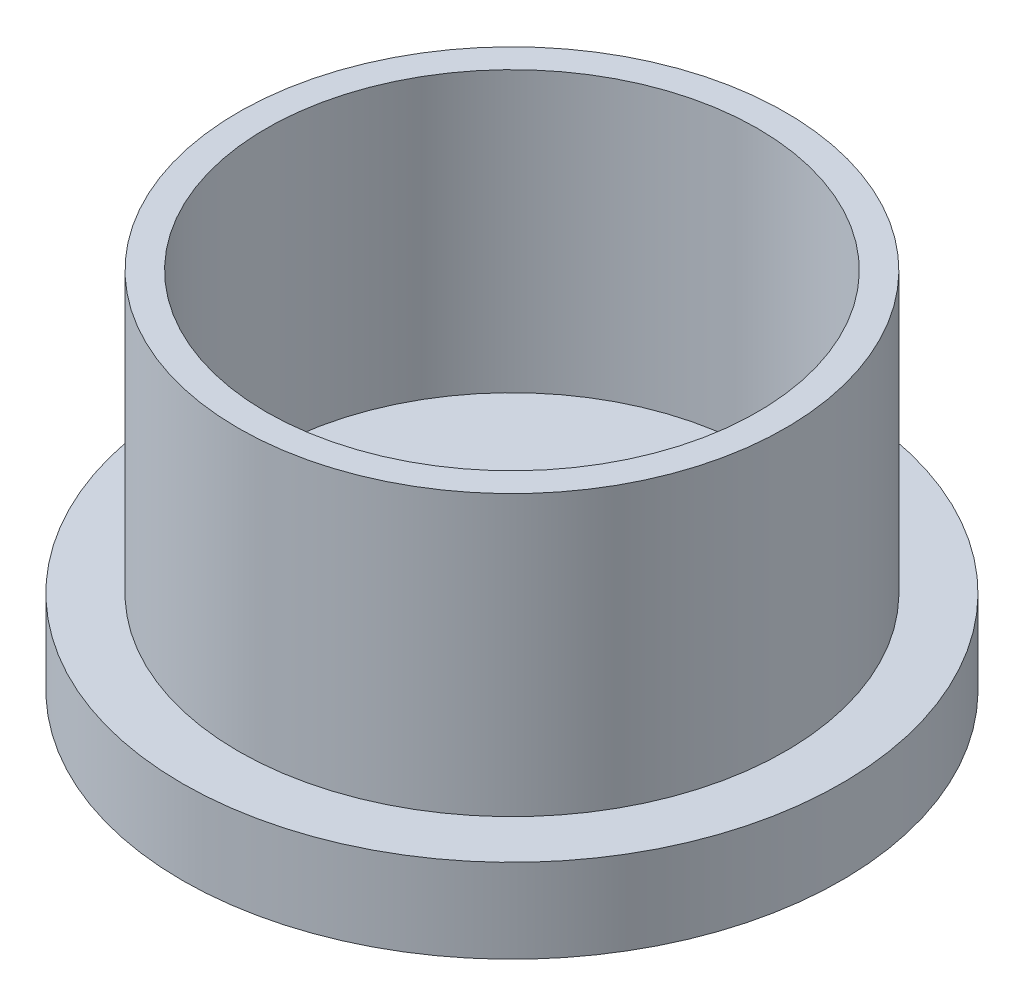
SolidWorks part; units mm, degrees
ref_plane "Front Plane" through (0, 0, 0) normal (0, 0, 1) x (1, 0, 0)
ref_plane "Top Plane" through (0, 0, 0) normal (0, 1, 0) x (1, 0, 0)
ref_plane "Right Plane" through (0, 0, 0) normal (1, 0, 0) x (0, 0, -1)
sketch "Sketch1" plane through (0, 0, 0) normal (0, 1, 0) x (1, 0, 0)
  circle A0 centre (0, 0) radius 11.78
  point P3 (0, 0)
  dimension "D1" = 23.56
extrude "Boss-Extrude1" add sketch "Sketch1" along normal blind 3
sketch "Sketch3" plane through (0, 3, 0) normal (0, 1, 0) x (1, 0, 0)
  line L1 (-7.78, 0.25) -> (7.78, 0.25)
  line L2 (-7.78, 0.25) -> (-7.78, -0.25)
  line L3 (-7.78, -0.25) -> (7.78, -0.25)
  line L4 (7.78, 0.25) -> (7.78, -0.25)
  line L5 (-7.78, 0.25) -> (7.78, -0.25) construction
  line L6 (-7.78, -0.25) -> (7.78, 0.25) construction
  point P0 (0, 0)
  dimension "D1" = 0.5
  dimension "D2" = 15.56
extrude "Cut-Extrude1" cut sketch "Sketch3" against normal blind 3 contours L3 L4 L1 L2
sketch "Sketch4" plane through (0, 3, 0) normal (0, 1, 0) x (1, 0, 0)
  line L1 (-0.25, 7.78) -> (0.25, 7.78)
  line L2 (-0.25, 7.78) -> (-0.25, -7.78)
  line L3 (-0.25, -7.78) -> (0.25, -7.78)
  line L4 (0.25, 7.78) -> (0.25, -7.78)
  line L5 (-0.25, 7.78) -> (0.25, -7.78) construction
  line L6 (-0.25, -7.78) -> (0.25, 7.78) construction
  point P0 (0, 0)
  dimension "D1" = 0.5
  dimension "D2" = 15.56
extrude "Cut-Extrude2" cut sketch "Sketch4" against normal blind 3
sketch "Sketch5" plane through (0, 3, 0) normal (0, 1, 0) x (1, 0, 0)
  circle A0 centre (0, 0) radius 9.78
  dimension "D1" = 19.56
extrude "Boss-Extrude3" add sketch "Sketch5" along normal blind 10
sketch "Sketch6" plane through (0, 13, 0) normal (0, 1, 0) x (1, 0, 0)
  circle A0 centre (0, 0) radius 8.78
  dimension "D1" = 17.56
extrude "Cut-Extrude3" cut sketch "Sketch6" against normal blind 10
